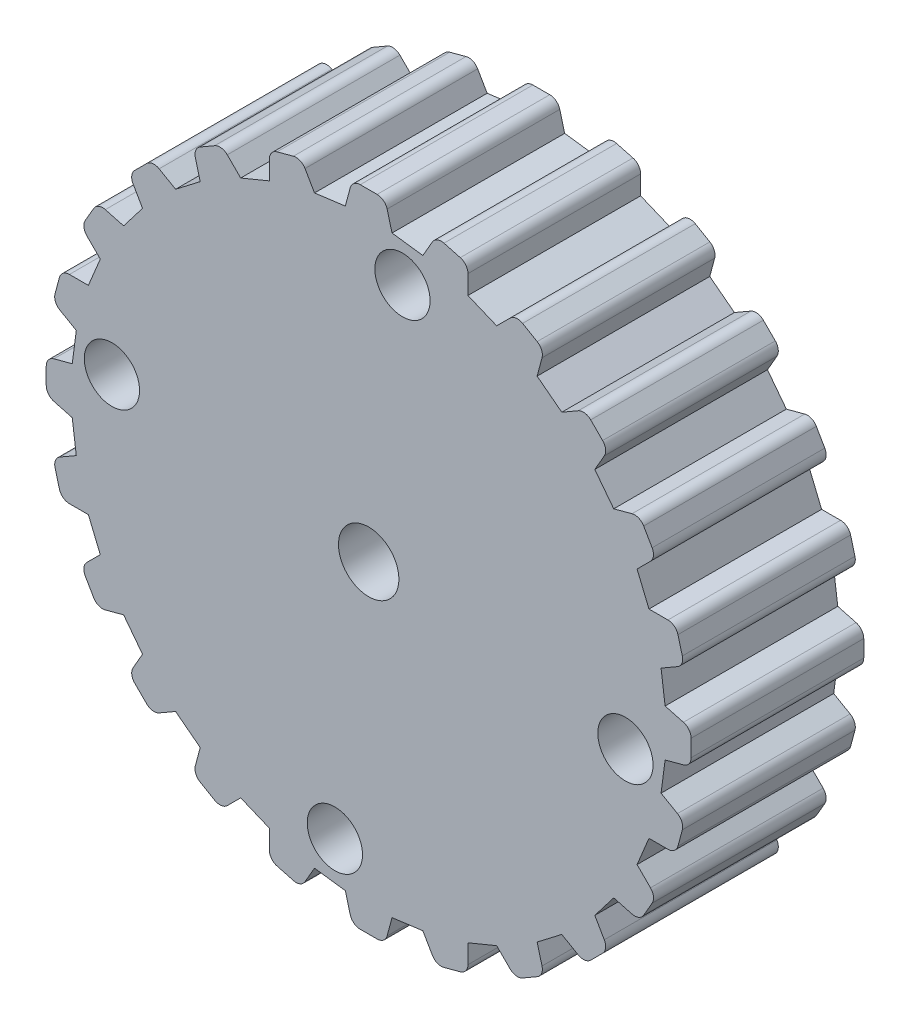
SolidWorks part; units mm, degrees
ref_plane "Plan de face" through (0, 0, 0) normal (0, 0, 1) x (1, 0, 0)
ref_plane "Plan de dessus" through (0, 0, 0) normal (0, 1, 0) x (1, 0, 0)
ref_plane "Plan de droite" through (0, 0, 0) normal (1, 0, 0) x (0, 0, -1)
sketch "Esquisse1" plane through (0, 0, 0) normal (0, 0, 1) x (1, 0, 0)
  line L0 (0, 0) -> (0, 19.1) construction
  line L1 (0, 0) -> (4.9434, 18.4492) construction
  line L2 (0, 0) -> (2.4931, 18.9366) construction
  line L3 (0.4889, 18.6759) -> (0, 18.6759)
  line L4 (1.0685, 18.2312) -> (1.3528, 17.1703)
  line L5 (1.3528, 17.1703) -> (3.1374, 16.9354)
  line L6 (3.6865, 17.8865) -> (3.1374, 16.9354)
  line L7 (4.3614, 18.1661) -> (4.8337, 18.0395)
  line L8 (5.306, 17.913) -> (4.8337, 18.0395)
  line L9 (5.7507, 17.3334) -> (5.7507, 16.2351)
  line L10 (5.7507, 16.2351) -> (7.4136, 15.5463)
  line L11 (8.1902, 16.3229) -> (7.4136, 15.5463)
  line L12 (8.9145, 16.4183) -> (9.3379, 16.1738)
  line L13 (9.7614, 15.9293) -> (9.3379, 16.1738)
  line L14 (10.0409, 15.2544) -> (9.7567, 14.1936)
  line L15 (9.7567, 14.1936) -> (11.1847, 13.0978)
  line L16 (12.1358, 13.6469) -> (11.1847, 13.0978)
  line L17 (12.8601, 13.5516) -> (13.2058, 13.2058)
  line L18 (13.5516, 12.8601) -> (13.2058, 13.2058)
  line L19 (13.6469, 12.1358) -> (13.0978, 11.1847)
  line L20 (13.0978, 11.1847) -> (14.1936, 9.7567)
  line L21 (15.2544, 10.0409) -> (14.1936, 9.7567)
  line L22 (15.9293, 9.7614) -> (16.1738, 9.3379)
  line L23 (16.4183, 8.9145) -> (16.1738, 9.3379)
  line L24 (16.3229, 8.1902) -> (15.5463, 7.4136)
  line L25 (15.5463, 7.4136) -> (16.2351, 5.7507)
  line L26 (17.3334, 5.7507) -> (16.2351, 5.7507)
  line L27 (17.913, 5.306) -> (18.0395, 4.8337)
  line L28 (18.1661, 4.3614) -> (18.0395, 4.8337)
  line L29 (17.8865, 3.6865) -> (16.9354, 3.1374)
  line L30 (16.9354, 3.1374) -> (17.1703, 1.3528)
  line L31 (18.2312, 1.0685) -> (17.1703, 1.3528)
  line L32 (18.6759, 0.4889) -> (18.6759, 0)
  line L33 (18.6759, -0.4889) -> (18.6759, 0)
  line L34 (18.2312, -1.0685) -> (17.1703, -1.3528)
  line L35 (17.1703, -1.3528) -> (16.9354, -3.1374)
  line L36 (17.8865, -3.6865) -> (16.9354, -3.1374)
  line L37 (18.1661, -4.3614) -> (18.0395, -4.8337)
  line L38 (17.913, -5.306) -> (18.0395, -4.8337)
  line L39 (17.3334, -5.7507) -> (16.2351, -5.7507)
  line L40 (16.2351, -5.7507) -> (15.5463, -7.4136)
  line L41 (16.3229, -8.1902) -> (15.5463, -7.4136)
  line L42 (16.4183, -8.9145) -> (16.1738, -9.3379)
  line L43 (15.9293, -9.7614) -> (16.1738, -9.3379)
  line L44 (15.2544, -10.0409) -> (14.1936, -9.7567)
  line L45 (14.1936, -9.7567) -> (13.0978, -11.1847)
  line L46 (13.6469, -12.1358) -> (13.0978, -11.1847)
  line L47 (13.5516, -12.8601) -> (13.2058, -13.2058)
  line L48 (12.8601, -13.5516) -> (13.2058, -13.2058)
  line L49 (12.1358, -13.6469) -> (11.1847, -13.0978)
  line L50 (11.1847, -13.0978) -> (9.7567, -14.1936)
  line L51 (10.0409, -15.2544) -> (9.7567, -14.1936)
  line L52 (9.7614, -15.9293) -> (9.3379, -16.1738)
  line L53 (8.9145, -16.4183) -> (9.3379, -16.1738)
  line L54 (8.1902, -16.3229) -> (7.4136, -15.5463)
  line L55 (7.4136, -15.5463) -> (5.7507, -16.2351)
  line L56 (5.7507, -17.3334) -> (5.7507, -16.2351)
  line L57 (5.306, -17.913) -> (4.8337, -18.0395)
  line L58 (4.3614, -18.1661) -> (4.8337, -18.0395)
  line L59 (3.6865, -17.8865) -> (3.1374, -16.9354)
  line L60 (3.1374, -16.9354) -> (1.3528, -17.1703)
  line L61 (1.0685, -18.2312) -> (1.3528, -17.1703)
  line L62 (0.4889, -18.6759) -> (0, -18.6759)
  line L63 (-0.4889, -18.6759) -> (0, -18.6759)
  line L64 (-1.0685, -18.2312) -> (-1.3528, -17.1703)
  line L65 (-1.3528, -17.1703) -> (-3.1374, -16.9354)
  line L66 (-3.6865, -17.8865) -> (-3.1374, -16.9354)
  line L67 (-4.3614, -18.1661) -> (-4.8337, -18.0395)
  line L68 (-5.306, -17.913) -> (-4.8337, -18.0395)
  line L69 (-5.7507, -17.3334) -> (-5.7507, -16.2351)
  line L70 (-5.7507, -16.2351) -> (-7.4136, -15.5463)
  line L71 (-8.1902, -16.3229) -> (-7.4136, -15.5463)
  line L72 (-8.9145, -16.4183) -> (-9.3379, -16.1738)
  line L73 (-9.7614, -15.9293) -> (-9.3379, -16.1738)
  line L74 (-10.0409, -15.2544) -> (-9.7567, -14.1936)
  line L75 (-9.7567, -14.1936) -> (-11.1847, -13.0978)
  line L76 (-12.1358, -13.6469) -> (-11.1847, -13.0978)
  line L77 (-12.8601, -13.5516) -> (-13.2058, -13.2058)
  line L78 (-13.5516, -12.8601) -> (-13.2058, -13.2058)
  line L79 (-13.6469, -12.1358) -> (-13.0978, -11.1847)
  line L80 (-13.0978, -11.1847) -> (-14.1936, -9.7567)
  line L81 (-15.2544, -10.0409) -> (-14.1936, -9.7567)
  line L82 (-15.9293, -9.7614) -> (-16.1738, -9.3379)
  line L83 (-16.4183, -8.9145) -> (-16.1738, -9.3379)
  line L84 (-16.3229, -8.1902) -> (-15.5463, -7.4136)
  line L85 (-15.5463, -7.4136) -> (-16.2351, -5.7507)
  line L86 (-17.3334, -5.7507) -> (-16.2351, -5.7507)
  line L87 (-17.913, -5.306) -> (-18.0395, -4.8337)
  line L88 (-18.1661, -4.3614) -> (-18.0395, -4.8337)
  line L89 (-17.8865, -3.6865) -> (-16.9354, -3.1374)
  line L90 (-16.9354, -3.1374) -> (-17.1703, -1.3528)
  line L91 (-18.2312, -1.0685) -> (-17.1703, -1.3528)
  line L92 (-18.6759, -0.4889) -> (-18.6759, 0)
  line L93 (-18.6759, 0.4889) -> (-18.6759, 0)
  line L94 (-18.2312, 1.0685) -> (-17.1703, 1.3528)
  line L95 (-17.1703, 1.3528) -> (-16.9354, 3.1374)
  line L96 (-17.8865, 3.6865) -> (-16.9354, 3.1374)
  line L97 (-18.1661, 4.3614) -> (-18.0395, 4.8337)
  line L98 (-17.913, 5.306) -> (-18.0395, 4.8337)
  line L99 (-17.3334, 5.7507) -> (-16.2351, 5.7507)
  line L100 (-16.2351, 5.7507) -> (-15.5463, 7.4136)
  line L101 (-16.3229, 8.1902) -> (-15.5463, 7.4136)
  line L102 (-16.4183, 8.9145) -> (-16.1738, 9.3379)
  line L103 (-15.9293, 9.7614) -> (-16.1738, 9.3379)
  line L104 (-15.2544, 10.0409) -> (-14.1936, 9.7567)
  line L105 (-14.1936, 9.7567) -> (-13.0978, 11.1847)
  line L106 (-13.6469, 12.1358) -> (-13.0978, 11.1847)
  line L107 (-13.5516, 12.8601) -> (-13.2058, 13.2058)
  line L108 (-12.8601, 13.5516) -> (-13.2058, 13.2058)
  line L109 (-12.1358, 13.6469) -> (-11.1847, 13.0978)
  line L110 (-11.1847, 13.0978) -> (-9.7567, 14.1936)
  line L111 (-10.0409, 15.2544) -> (-9.7567, 14.1936)
  line L112 (-9.7614, 15.9293) -> (-9.3379, 16.1738)
  line L113 (-8.9145, 16.4183) -> (-9.3379, 16.1738)
  line L114 (-8.1902, 16.3229) -> (-7.4136, 15.5463)
  line L115 (-7.4136, 15.5463) -> (-5.7507, 16.2351)
  line L116 (-5.7507, 17.3334) -> (-5.7507, 16.2351)
  line L117 (-5.306, 17.913) -> (-4.8337, 18.0395)
  line L118 (-4.3614, 18.1661) -> (-4.8337, 18.0395)
  line L119 (-3.6865, 17.8865) -> (-3.1374, 16.9354)
  line L120 (-3.1374, 16.9354) -> (-1.3528, 17.1703)
  line L121 (-1.0685, 18.2312) -> (-1.3528, 17.1703)
  line L122 (-0.4889, 18.6759) -> (0, 18.6759)
  circle A0 centre (0, 0) radius 19.1 construction
  circle A1 centre (0, 0) radius 18.7 construction
  circle A2 centre (0, 0) radius 17.2 construction
  arc A3 (4.3614, 18.1661) -> (3.6865, 17.8865) centre (4.2061, 17.5865) ccw
  arc A4 (1.0685, 18.2312) -> (0.4889, 18.6759) centre (0.4889, 18.0759) ccw
  arc A5 (8.9145, 16.4183) -> (8.1902, 16.3229) centre (8.6145, 15.8986) ccw
  arc A6 (5.7507, 17.3334) -> (5.306, 17.913) centre (5.1507, 17.3334) ccw
  arc A7 (12.8601, 13.5516) -> (12.1358, 13.6469) centre (12.4358, 13.1273) ccw
  arc A8 (10.0409, 15.2544) -> (9.7614, 15.9293) centre (9.4614, 15.4097) ccw
  arc A9 (15.9293, 9.7614) -> (15.2544, 10.0409) centre (15.4097, 9.4614) ccw
  arc A10 (13.6469, 12.1358) -> (13.5516, 12.8601) centre (13.1273, 12.4358) ccw
  arc A11 (17.913, 5.306) -> (17.3334, 5.7507) centre (17.3334, 5.1507) ccw
  arc A12 (16.3229, 8.1902) -> (16.4183, 8.9145) centre (15.8986, 8.6145) ccw
  arc A13 (18.6759, 0.4889) -> (18.2312, 1.0685) centre (18.0759, 0.4889) ccw
  arc A14 (17.8865, 3.6865) -> (18.1661, 4.3614) centre (17.5865, 4.2061) ccw
  arc A15 (18.1661, -4.3614) -> (17.8865, -3.6865) centre (17.5865, -4.2061) ccw
  arc A16 (18.2312, -1.0685) -> (18.6759, -0.4889) centre (18.0759, -0.4889) ccw
  arc A17 (16.4183, -8.9145) -> (16.3229, -8.1902) centre (15.8986, -8.6145) ccw
  arc A18 (17.3334, -5.7507) -> (17.913, -5.306) centre (17.3334, -5.1507) ccw
  arc A19 (13.5516, -12.8601) -> (13.6469, -12.1358) centre (13.1273, -12.4358) ccw
  arc A20 (15.2544, -10.0409) -> (15.9293, -9.7614) centre (15.4097, -9.4614) ccw
  arc A21 (9.7614, -15.9293) -> (10.0409, -15.2544) centre (9.4614, -15.4097) ccw
  arc A22 (12.1358, -13.6469) -> (12.8601, -13.5516) centre (12.4358, -13.1273) ccw
  arc A23 (5.306, -17.913) -> (5.7507, -17.3334) centre (5.1507, -17.3334) ccw
  arc A24 (8.1902, -16.3229) -> (8.9145, -16.4183) centre (8.6145, -15.8986) ccw
  arc A25 (0.4889, -18.6759) -> (1.0685, -18.2312) centre (0.4889, -18.0759) ccw
  arc A26 (3.6865, -17.8865) -> (4.3614, -18.1661) centre (4.2061, -17.5865) ccw
  arc A27 (-4.3614, -18.1661) -> (-3.6865, -17.8865) centre (-4.2061, -17.5865) ccw
  arc A28 (-1.0685, -18.2312) -> (-0.4889, -18.6759) centre (-0.4889, -18.0759) ccw
  arc A29 (-8.9145, -16.4183) -> (-8.1902, -16.3229) centre (-8.6145, -15.8986) ccw
  arc A30 (-5.7507, -17.3334) -> (-5.306, -17.913) centre (-5.1507, -17.3334) ccw
  arc A31 (-12.8601, -13.5516) -> (-12.1358, -13.6469) centre (-12.4358, -13.1273) ccw
  arc A32 (-10.0409, -15.2544) -> (-9.7614, -15.9293) centre (-9.4614, -15.4097) ccw
  arc A33 (-15.9293, -9.7614) -> (-15.2544, -10.0409) centre (-15.4097, -9.4614) ccw
  arc A34 (-13.6469, -12.1358) -> (-13.5516, -12.8601) centre (-13.1273, -12.4358) ccw
  arc A35 (-17.913, -5.306) -> (-17.3334, -5.7507) centre (-17.3334, -5.1507) ccw
  arc A36 (-16.3229, -8.1902) -> (-16.4183, -8.9145) centre (-15.8986, -8.6145) ccw
  arc A37 (-18.6759, -0.4889) -> (-18.2312, -1.0685) centre (-18.0759, -0.4889) ccw
  arc A38 (-17.8865, -3.6865) -> (-18.1661, -4.3614) centre (-17.5865, -4.2061) ccw
  arc A39 (-18.1661, 4.3614) -> (-17.8865, 3.6865) centre (-17.5865, 4.2061) ccw
  arc A40 (-18.2312, 1.0685) -> (-18.6759, 0.4889) centre (-18.0759, 0.4889) ccw
  arc A41 (-16.4183, 8.9145) -> (-16.3229, 8.1902) centre (-15.8986, 8.6145) ccw
  arc A42 (-17.3334, 5.7507) -> (-17.913, 5.306) centre (-17.3334, 5.1507) ccw
  arc A43 (-13.5516, 12.8601) -> (-13.6469, 12.1358) centre (-13.1273, 12.4358) ccw
  arc A44 (-15.2544, 10.0409) -> (-15.9293, 9.7614) centre (-15.4097, 9.4614) ccw
  arc A45 (-9.7614, 15.9293) -> (-10.0409, 15.2544) centre (-9.4614, 15.4097) ccw
  arc A46 (-12.1358, 13.6469) -> (-12.8601, 13.5516) centre (-12.4358, 13.1273) ccw
  arc A47 (-5.306, 17.913) -> (-5.7507, 17.3334) centre (-5.1507, 17.3334) ccw
  arc A48 (-8.1902, 16.3229) -> (-8.9145, 16.4183) centre (-8.6145, 15.8986) ccw
  arc A49 (-0.4889, 18.6759) -> (-1.0685, 18.2312) centre (-0.4889, 18.0759) ccw
  arc A50 (-3.6865, 17.8865) -> (-4.3614, 18.1661) centre (-4.2061, 17.5865) ccw
  point P14 (2.2451, 17.0529)
  point P16 (3.9167, 18.2852)
  point P20 (0.9493, 18.6759)
  point P29 (6.5822, 15.8907)
  point P40 (10.4707, 13.6457)
  point P51 (13.6457, 10.4707)
  point P62 (15.8907, 6.5822)
  point P73 (17.0529, 2.2451)
  point P84 (17.0529, -2.2451)
  point P95 (15.8907, -6.5822)
  point P106 (13.6457, -10.4707)
  point P117 (10.4707, -13.6457)
  point P128 (6.5822, -15.8907)
  point P139 (2.2451, -17.0529)
  point P150 (-2.2451, -17.0529)
  point P161 (-6.5822, -15.8907)
  point P172 (-10.4707, -13.6457)
  point P183 (-13.6457, -10.4707)
  point P194 (-15.8907, -6.5822)
  point P205 (-17.0529, -2.2451)
  point P216 (-17.0529, 2.2451)
  point P227 (-15.8907, 6.5822)
  point P238 (-13.6457, 10.4707)
  point P249 (-10.4707, 13.6457)
  point P260 (-6.5822, 15.8907)
  point P271 (-2.2451, 17.0529)
  point P276 (0, 0)
  dimension "D1" = 38.2
  dimension "D2" = 37.4
  dimension "D5" = 1.5
  dimension "D8" = 0.6
  dimension "D3" = 15
  dimension "D4" = 7.5
  dimension "D6" = 15
  dimension "D7" = 1.8
  dimension "D9" = 24
extrude "Boss.-Extru.1" add sketch "Esquisse1" along normal blind 10
sketch "Esquisse2" plane through (0, 0, 10) normal (0, 0, 1) x (1, 0, 0)
  line L0 (0, 0) -> (1.9579, 14.8717) construction
  line L1 (0, 0) -> (0, 18.6759) construction
  line L3 (0.4889, 18.6759) -> (-0.4889, 18.6759) construction
  circle A0 centre (0, 0) radius 15 construction
  circle A1 centre (14.8717, -1.9579) radius 1.6
  circle A2 centre (0, 0) radius 1.75
  circle A3 centre (1.9579, 14.8717) radius 1.6
  circle A4 centre (-1.9579, -14.8717) radius 1.6
  circle A5 centre (-14.8717, 1.9579) radius 1.6
  point P3 (0, 18.4492)
  point P6 (0, 18.6759)
  point P15 (0, 0)
  point P19 (0, 0)
  dimension "D1" = 30
  dimension "D2" = 7.5
  dimension "D3" = 3.5
  dimension "D5" = 3.2
  dimension "D4" = 4
extrude "Enlèv. mat.-Extru.1" cut sketch "Esquisse2" against normal through all
